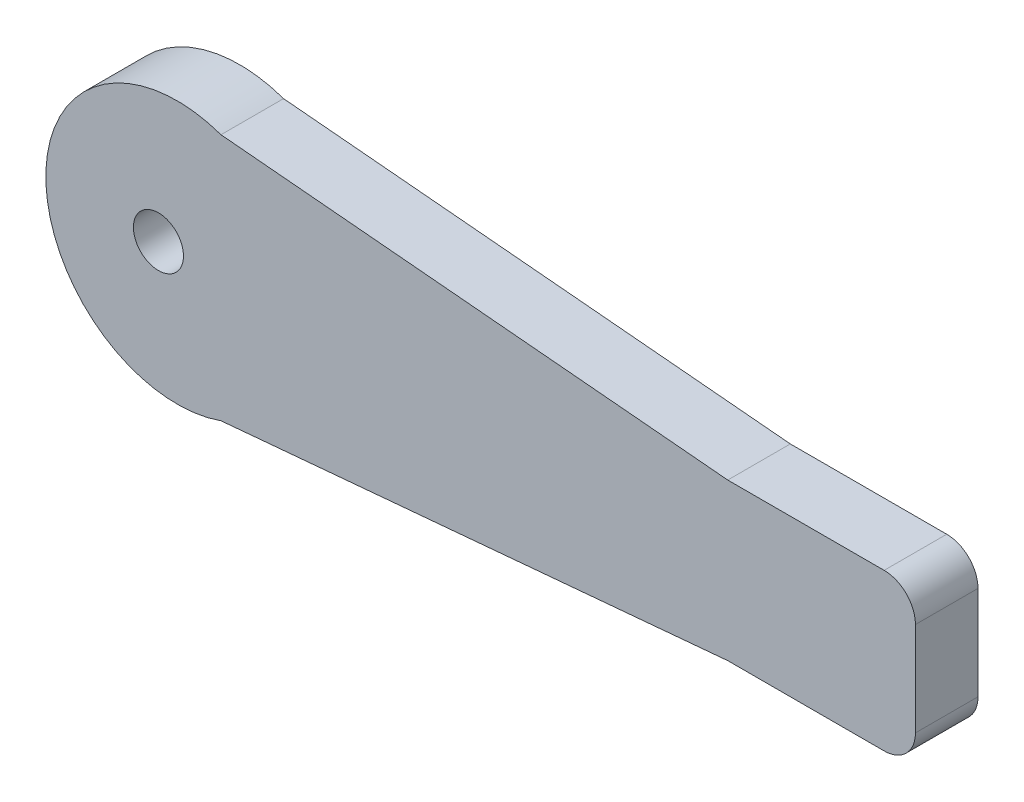
SolidWorks part; units mm, degrees
ref_plane "前视基准面" through (0, 0, 0) normal (0, 0, 1) x (1, 0, 0)
ref_plane "上视基准面" through (0, 0, 0) normal (0, 1, 0) x (1, 0, 0)
ref_plane "右视基准面" through (0, 0, 0) normal (1, 0, 0) x (0, 0, -1)
sketch "草图1" plane through (0, 0, 0) normal (0, 0, 1) x (1, 0, 0)
  line L0 (0, 0) -> (19125.223, 0) construction
  line L1 (0, 0) -> (0, 19125.223) construction
  line L2 (-41.5, 0) -> (-41.5, 50000)
  line L3 (-69.5, 21) -> (69.5, 21)
  line L4 (-69.5, 21) -> (-69.5, -21)
  line L5 (-69.5, -21) -> (69.5, -21)
  line L6 (69.5, 21) -> (69.5, -21)
  line L7 (69.5, 12.5) -> (39.5, 12.5)
  line L8 (69.5, 12.5) -> (69.5, -12.5)
  line L9 (69.5, -12.5) -> (39.5, -12.5)
  line L10 (39.5, 12.5) -> (39.5, -12.5)
  line L11 (-41.5, 19.799) -> (39.5, 12.5)
  line L12 (39.5, -12.5) -> (-41.5, -19.799)
  circle A0 centre (-48.5, 0) radius 21
  dimension "D1" = 42
  dimension "D2" = 139
  dimension "D3" = 28
extrude "凸台-拉伸1" add sketch "草图1" along normal blind 10 contours L2 A0 | L2 A0 | A0 L12 L10 L11 | L7 L10 L9 L6
fillet "圆角1" radius 5 2 edges at (69.5, -12.5, 5) (69.5, 12.5, 5)
sketch "草图2" plane through (0, 0, 10) normal (0, 0, 1) x (1, 0, 0)
  line L0 (0, 0) -> (50000, 0) construction
  line L1 (0, 0) -> (0, 50000) construction
  line L2 (69.5, 7.5) -> (69.5, -7.5) construction
  circle A0 centre (-51.5, 0) radius 4
  dimension "D1" = 121
extrude "切除-拉伸1" cut sketch "草图2" against normal blind 14 contours A0
